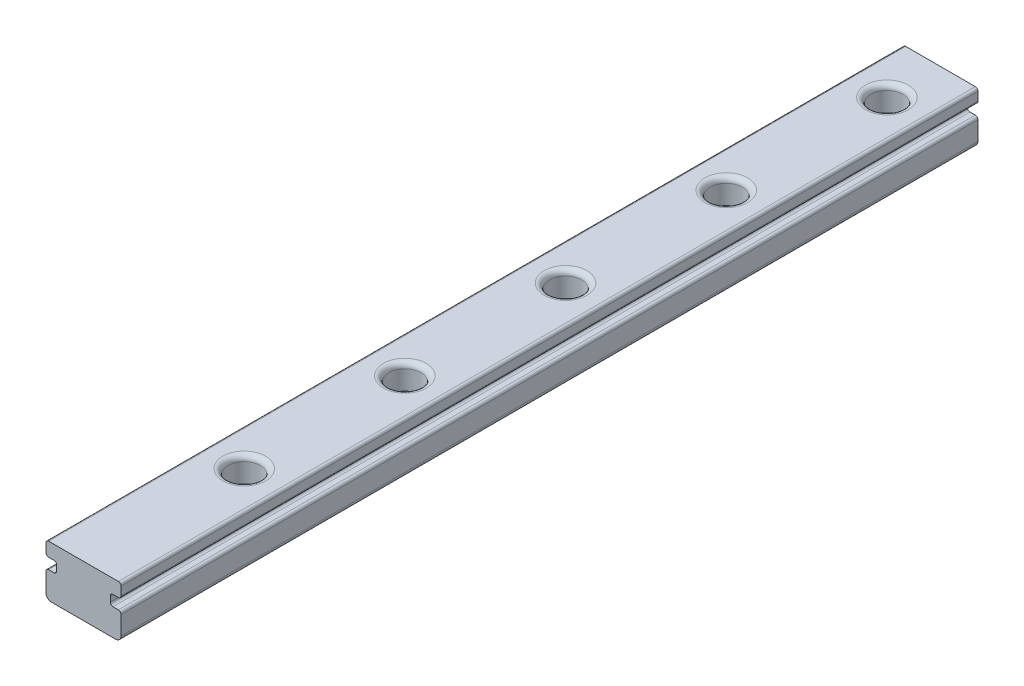
SolidWorks part; units mm, degrees
material "201 退火不锈钢 (SS)"
ref_plane "前视基准面" through (0, 0, 0) normal (0, 0, 1) x (1, 0, 0)
ref_plane "上视基准面" through (0, 0, 0) normal (0, 1, 0) x (1, 0, 0)
ref_plane "右视基准面" through (0, 0, 0) normal (1, 0, 0) x (0, 0, -1)
sketch "草图1" plane through (0, 0, 0) normal (0, 0, 1) x (1, 0, 0)
  line L0 (0, 0) -> (7, 0)
  line L1 (0, 3.5) -> (0, 4.8)
  line L2 (0, 4.8) -> (7, 4.8)
  line L3 (7, 4.8) -> (7, 3.5)
  line L4 (0, 4.8) -> (0, 3.5)
  line L5 (0, 2.5) -> (1, 2.5)
  line L6 (1, 2.5) -> (1, 3.5)
  line L7 (1, 3.5) -> (0, 3.5)
  line L8 (7, 3.5) -> (6, 3.5)
  line L9 (6, 3.5) -> (6, 2.5)
  line L10 (6, 2.5) -> (7, 2.5)
  line L11 (0, 2.5) -> (0, 0)
  line L12 (7, 2.5) -> (7, 0)
extrude "凸台-拉伸1" add sketch "草图1" along normal blind 80 contours L12 L10 L9 L8 L3 L2 L1 L7 L6 L5 L11 L0
fillet "圆角1" radius 0.25 10 edges at (7, 2.5, 40) (0, 2.5, 40) (1, 3.5, 40) (1, 2.5, 40) (6, 2.5, 40) (6, 3.5, 40) (7, 4.8, 40) (0, 4.8, 40) (0, 3.5, 40) (7, 3.5, 40)
fillet "圆角2" radius 0.5 2 edges at (0, 0, 40) (7, 0, 40)
sketch "草图2" plane through (0, 4.8, 0) normal (0, 1, 0) x (1, 0, 0)
  line L0 (0.25, 0) -> (6.75, 0) construction
  line L1 (3.5, 0) -> (3.5, -6.7471) construction
  circle A0 centre (3.5, -5) radius 1.5
  dimension "D1" = 3
  dimension "D2" = 5
extrude "切除-拉伸1" cut sketch "草图2" against normal blind 2.3
sketch "草图3" plane through (0, 2.5, 0) normal (0, 1, 0) x (1, 0, 0)
  line L0 (0.5, 0) -> (6.5, 0) construction
  line L1 (3.5, 0) -> (3.5, -4.4975) construction
  circle A1 centre (3.5, -5) radius 1.2
  dimension "D1" = 2.4
extrude "切除-拉伸2" cut sketch "草图3" against normal through all
fillet "圆角3" radius 0.5 1 edges at (3.5, 4.8, 6.5)
pattern_linear "阵列(线性)2" count 5 spacing 15 along (0, 0, 1) of "切除-拉伸1", "切除-拉伸2", "圆角3"
sketch "草图4" plane through (0, 0, 80) normal (0, 0, 1) x (1, 0, 0)
  line L1 (-0.1519, 5.0948) -> (7.4555, 5.0948)
  line L2 (-0.1519, 5.0948) -> (-0.1519, -0.4394)
  line L3 (-0.1519, -0.4394) -> (7.4555, -0.4394)
  line L4 (7.4555, 5.0948) -> (7.4555, -0.4394)
extrude "切除-拉伸3" [suppressed] cut sketch "草图4" against normal blind 30
